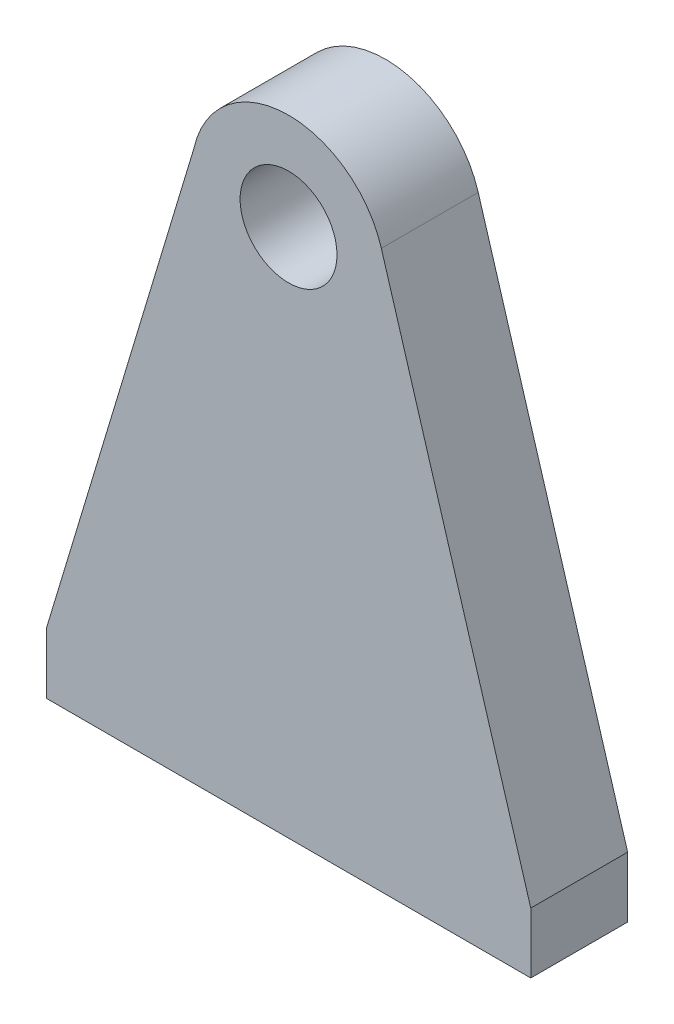
SolidWorks part; units mm, degrees
ref_plane "Front Plane" through (0, 0, 0) normal (0, 0, 1) x (1, 0, 0)
ref_plane "Top Plane" through (0, 0, 0) normal (0, 1, 0) x (1, 0, 0)
ref_plane "Right Plane" through (0, 0, 0) normal (1, 0, 0) x (0, 0, -1)
sketch "Sketch1" plane through (0, 0, 0) normal (0, 0, 1) x (1, 0, 0)
  line L0 (-16.5787, 216.1132) -> (-16.5787, -3.8868) construction
  line L1 (21.7251, 227.6379) -> (83.4213, 22.583)
  line L2 (83.4213, 22.583) -> (83.4213, -2.417)
  line L3 (-116.5787, 22.583) -> (-116.5787, -2.417)
  line L4 (-55.649, 224.687) -> (-116.5787, 22.583)
  line L5 (-116.5787, -2.417) -> (83.4213, -2.417)
  circle A0 centre (-16.5787, 216.1132) radius 20
  arc A1 (21.7251, 227.6379) -> (-55.649, 224.687) centre (-16.5787, 216.1132) ccw
  point P3 (-83.2773, 22.583)
  dimension "D1" = 40
  dimension "D2" = 80
  dimension "D3" = 25
  dimension "D4" = 220
  dimension "D5" = 200
  dimension "D6" = 100
extrude "Boss-Extrude1" add sketch "Sketch1" along normal blind 40
